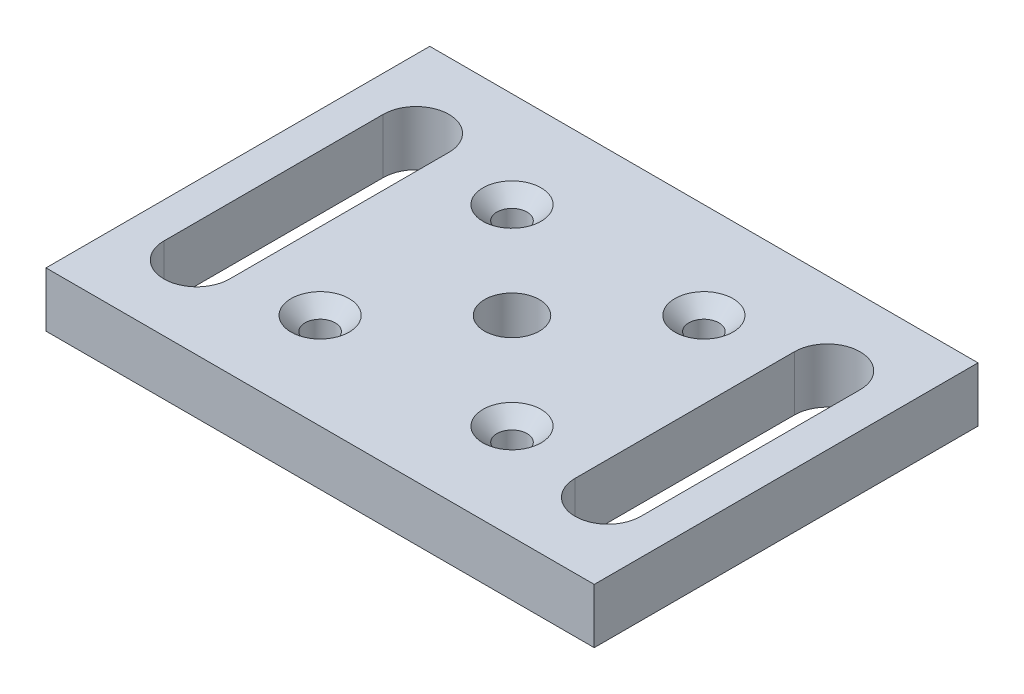
SolidWorks part; units mm, degrees
ref_plane "Front Plane" through (0, 0, 0) normal (0, 0, 1) x (1, 0, 0)
ref_plane "Top Plane" through (0, 0, 0) normal (0, 1, 0) x (1, 0, 0)
ref_plane "Right Plane" through (0, 0, 0) normal (1, 0, 0) x (0, 0, -1)
sketch "Sketch1" plane through (0, 0, 0) normal (0, 1, 0) x (1, 0, 0)
  line L0 (0, 35) -> (100, 35) construction
  line L1 (0, 0) -> (100, 0)
  line L2 (0, 0) -> (0, 70)
  line L3 (0, 70) -> (100, 70)
  line L4 (100, 0) -> (100, 70)
  line L5 (50, 70) -> (50, 0) construction
  line L6 (87.5, 70) -> (87.5, 0) construction
  line L7 (12.5, 70) -> (12.5, 0) construction
  line L8 (0, 55) -> (100, 55) construction
  line L9 (0, 15) -> (100, 15) construction
  line L10 (12.5, 55) -> (12.5, 15) construction
  line L11 (18.5, 55) -> (18.5, 15)
  line L12 (6.5, 55) -> (6.5, 15)
  line L13 (87.5, 55) -> (87.5, 15) construction
  line L14 (93.5, 55) -> (93.5, 15)
  line L15 (81.5, 55) -> (81.5, 15)
  line L16 (30, 70) -> (30, 0) construction
  line L17 (70, 0) -> (70, 70) construction
  circle A0 centre (50, 35) radius 5
  arc A1 (18.5, 55) -> (6.5, 55) centre (12.5, 55) ccw
  arc A2 (6.5, 15) -> (18.5, 15) centre (12.5, 15) ccw
  arc A3 (93.5, 55) -> (81.5, 55) centre (87.5, 55) ccw
  arc A4 (81.5, 15) -> (93.5, 15) centre (87.5, 15) ccw
  point P21 (12.5, 35)
  point P26 (87.5, 35)
  dimension "D3" = 10
  dimension "D8" = 6
  dimension "D9" = 6
  dimension "D1" = 100
  dimension "D2" = 70
  dimension "D4" = 37.5
  dimension "D5" = 37.5
  dimension "D6" = 20
  dimension "D7" = 20
  dimension "D10" = 20
  dimension "D11" = 20
extrude "Boss-Extrude1" add sketch "Sketch1" along normal blind 10
hole_wizard "CSK for M5 Countersunk Flat Head Screw1" positions "Sketch4" profile "Sketch5" countersink size "M5" standard "ISO" end condition through all
sketch "Sketch4" plane through (0, 10, 0) normal (0, 1, 0) x (1, 0, 0)
  circle A0 centre (50, 35) radius 5 construction
  point P0 (32.5, 52.5)
  point P2 (67.5, 52.5)
  point P4 (67.5, 17.5)
  point P6 (32.5, 17.5)
  dimension "D3" = 17.5
  dimension "D4" = 17.5
  dimension "D2" = 17.5
  dimension "D5" = 17.5
  dimension "D6" = 17.5
  dimension "D7" = 17.5
  dimension "D1" = 17.5
  dimension "D8" = 17.5
sketch "Sketch5" plane through (32.5, 10, -52.5) normal (1, 0, 0) x (0, 0, 1)
  line L0 (0, 0) -> (0, 10)
  line L1 (0, 10) -> (2.75, 10)
  line L2 (2.75, 10) -> (2.75, 2.55)
  line L3 (2.75, 2.55) -> (5.3, 0)
  line L5 (5.3, 0) -> (0, 0)
  line L6 (-2.75, 2.55) -> (-5.3, 0) construction
  line L11 (0, -6.35) -> (0, 107.95) construction
  dimension "Thru Hole Dia." = 5.5
  dimension "Thru Hole Depth" = 10
  dimension "Near C'Sink Dia." = 10.6
  dimension "Near C'Sink Angle" = 90
